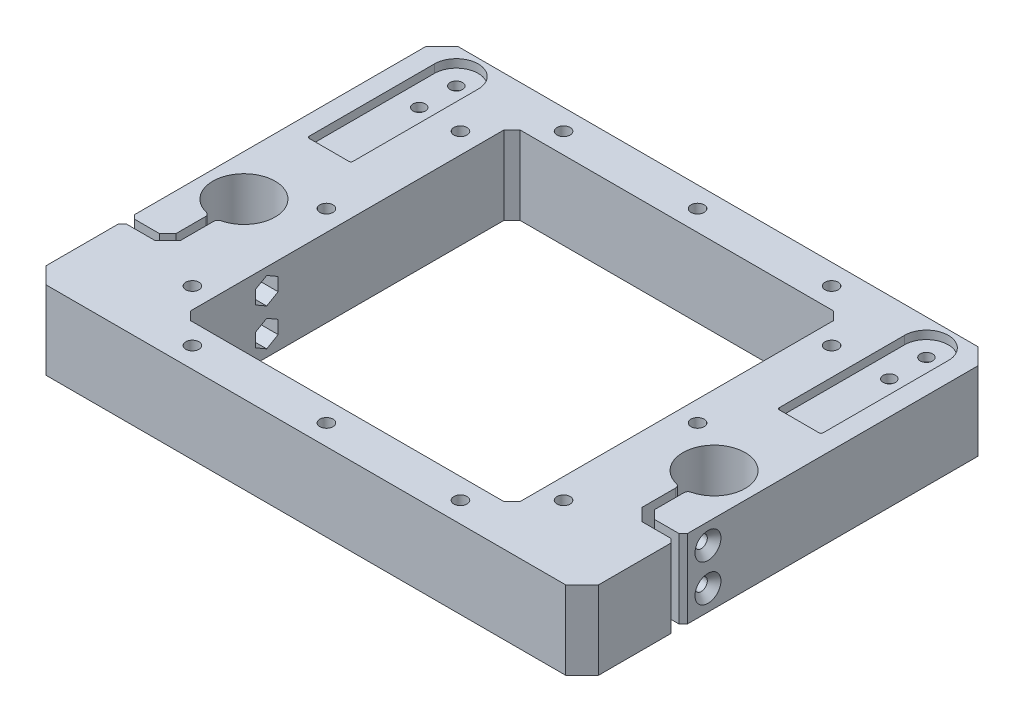
SolidWorks part; units mm, degrees
ref_plane "Front" through (0, 0, 0) normal (0, 0, 1) x (1, 0, 0)
ref_plane "Top" through (0, 0, 0) normal (0, 1, 0) x (1, 0, 0)
ref_plane "Right" through (0, 0, 0) normal (1, 0, 0) x (0, 0, -1)
sketch "Sketch1" plane through (0, 0, 0) normal (0, 1, 0) x (1, 0, 0)
  line L36 (-50, 46) -> (-50, -46)
  line L37 (-46, 50) -> (-50, 46)
  line L38 (46, 50) -> (-46, 50)
  line L39 (50, 46) -> (46, 50)
  line L40 (50, -46) -> (50, 46)
  line L41 (46, -50) -> (50, -46)
  line L42 (-46, -50) -> (46, -50)
  line L43 (-50, -46) -> (-46, -50)
  line L44 (-50, 46) -> (-50, -46)
  line L45 (-46, 50) -> (-50, 46)
  line L46 (46, 50) -> (-46, 50)
  line L47 (50, 46) -> (46, 50)
  line L48 (50, -46) -> (50, 46)
  line L49 (46, -50) -> (50, -46)
  line L50 (-46, -50) -> (46, -50)
  line L51 (-50, -46) -> (-46, -50)
  circle A2 centre (-45, 0) radius 1.6 construction
  circle A5 centre (-45, -32.5) radius 1.6 construction
  circle A6 centre (-32.5, -45) radius 1.6 construction
  circle A7 centre (0, -45) radius 1.6 construction
  circle A8 centre (32.5, -45) radius 1.6 construction
  circle A9 centre (45, -32.5) radius 1.6 construction
  circle A10 centre (45, 0) radius 1.6 construction
  circle A11 centre (45, 32.5) radius 1.6 construction
  circle A12 centre (32.5, 45) radius 1.6 construction
  circle A13 centre (0, 45) radius 1.6 construction
  circle A14 centre (-32.5, 45) radius 1.6 construction
  circle A15 centre (-45, 32.5) radius 1.6 construction
  circle A18 centre (-45, 0) radius 1.6
  circle A21 centre (-45, -32.5) radius 1.6
  circle A22 centre (-32.5, -45) radius 1.6
  circle A23 centre (0, -45) radius 1.6
  circle A24 centre (32.5, -45) radius 1.6
  circle A25 centre (45, -32.5) radius 1.6
  circle A26 centre (45, 0) radius 1.6
  circle A27 centre (45, 32.5) radius 1.6
  circle A28 centre (32.5, 45) radius 1.6
  circle A29 centre (0, 45) radius 1.6
  circle A30 centre (-32.5, 45) radius 1.6
  circle A31 centre (-45, 32.5) radius 1.6
  dimension "D1" = 0
extrude "Boss-Extrude2" add sketch "Sketch1" against normal blind 19
sketch "Sketch3" plane through (0, -19, 0) normal (0, 1, 0) x (1, 0, 0)
  line L1 (-40, -40) -> (40, -40)
  line L2 (-40, -40) -> (-40, 40)
  line L3 (-40, 40) -> (40, 40)
  line L4 (40, -40) -> (40, 40)
  line L5 (-40, -40) -> (40, 40) construction
  line L6 (-40, 40) -> (40, -40) construction
  line L7 (-46, 50) -> (46, 50) construction
  point P0 (0, 0)
  dimension "D1" = 10
extrude "Cut-Extrude2" cut sketch "Sketch3" along normal through all contours L4 L1 L2 L3
chamfer "Chamfer1" distance 2 angle 45 4 edges at (-40, -9.5, 40) (40, -9.5, 40) (40, -9.5, -40) (-40, -9.5, -40)
sketch "Sketch4" plane through (0, 0, 0) normal (0, 1, 0) x (1, 0, 0)
  line L1 (67, 46) -> (67, -46)
  line L3 (50, -46) -> (50, 46)
  line L6 (50, 46) -> (46, 50)
  line L7 (46, 50) -> (63, 50)
  line L8 (63, 50) -> (67, 46)
  line L9 (50, -46) -> (46, -50)
  line L10 (46, -50) -> (63, -50)
  line L11 (63, -50) -> (67, -46)
  dimension "D1" = 17
extrude "Boss-Extrude3" add sketch "Sketch4" against normal up to surface (19 mm away) up to face at (0, -19, 0)
sketch "Sketch5" plane through (0, -19, 0) normal (0, -1, 0) x (1, 0, 0)
  line L0 (67, -46) -> (67, 46) construction
  line L3 (63, -50) -> (-46, -50) construction
  line L4 (50, 46) -> (50, -46) construction
  circle A0 centre (57, -43.5) radius 10 construction
  circle A1 centre (57, -43.5) radius 1.5
  circle A2 centre (57, -34.5) radius 1.5
  circle A3 centre (57, 8) radius 7.55
  dimension "D1" = 3
  dimension "D2" = 9
  dimension "D3" = 15.1
  dimension "D4" = 8
  dimension "D5" = 7
  dimension "D6" = 6.5
extrude "Cut-Extrude3" cut sketch "Sketch5" against normal through all
sketch "Sketch2" plane through (0, -19, 0) normal (0, 1, 0) x (1, 0, 0)
  line L1 (-29.2957, 45) -> (-30.8979, 47.775)
  line L2 (-30.8979, 47.775) -> (-34.1021, 47.775)
  line L3 (-34.1021, 47.775) -> (-35.7043, 45)
  line L4 (-35.7043, 45) -> (-34.1021, 42.225)
  line L5 (-34.1021, 42.225) -> (-30.8979, 42.225)
  line L6 (-30.8979, 42.225) -> (-29.2957, 45)
  line L7 (3.2043, 45) -> (1.6021, 47.775)
  line L8 (1.6021, 47.775) -> (-1.6021, 47.775)
  line L9 (-1.6021, 47.775) -> (-3.2043, 45)
  line L10 (-3.2043, 45) -> (-1.6021, 42.225)
  line L11 (-1.6021, 42.225) -> (1.6021, 42.225)
  line L12 (1.6021, 42.225) -> (3.2043, 45)
  line L13 (35.7043, 45) -> (34.1021, 47.775)
  line L14 (34.1021, 47.775) -> (30.8979, 47.775)
  line L15 (30.8979, 47.775) -> (29.2957, 45)
  line L16 (29.2957, 45) -> (30.8979, 42.225)
  line L17 (30.8979, 42.225) -> (34.1021, 42.225)
  line L18 (34.1021, 42.225) -> (35.7043, 45)
  line L19 (45, 35.7043) -> (42.225, 34.1021)
  line L20 (42.225, 34.1021) -> (42.225, 30.8979)
  line L21 (42.225, 30.8979) -> (45, 29.2957)
  line L22 (45, 29.2957) -> (47.775, 30.8979)
  line L23 (47.775, 30.8979) -> (47.775, 34.1021)
  line L24 (47.775, 34.1021) -> (45, 35.7043)
  line L25 (45, 3.2043) -> (42.225, 1.6021)
  line L26 (42.225, 1.6021) -> (42.225, -1.6021)
  line L27 (42.225, -1.6021) -> (45, -3.2043)
  line L28 (45, -3.2043) -> (47.775, -1.6021)
  line L29 (47.775, -1.6021) -> (47.775, 1.6021)
  line L30 (47.775, 1.6021) -> (45, 3.2043)
  line L31 (45, -29.2957) -> (42.225, -30.8979)
  line L32 (42.225, -30.8979) -> (42.225, -34.1021)
  line L33 (42.225, -34.1021) -> (45, -35.7043)
  line L34 (45, -35.7043) -> (47.775, -34.1021)
  line L35 (47.775, -34.1021) -> (47.775, -30.8979)
  line L36 (47.775, -30.8979) -> (45, -29.2957)
  line L37 (30.8979, -42.225) -> (29.2957, -45)
  line L38 (29.2957, -45) -> (30.8979, -47.775)
  line L39 (30.8979, -47.775) -> (34.1021, -47.775)
  line L40 (34.1021, -47.775) -> (35.7043, -45)
  line L41 (35.7043, -45) -> (34.1021, -42.225)
  line L42 (34.1021, -42.225) -> (30.8979, -42.225)
  line L43 (-1.6021, -42.225) -> (-3.2043, -45)
  line L44 (-3.2043, -45) -> (-1.6021, -47.775)
  line L45 (-1.6021, -47.775) -> (1.6021, -47.775)
  line L46 (1.6021, -47.775) -> (3.2043, -45)
  line L47 (3.2043, -45) -> (1.6021, -42.225)
  line L48 (1.6021, -42.225) -> (-1.6021, -42.225)
  line L49 (-34.1021, -42.225) -> (-35.7043, -45)
  line L50 (-35.7043, -45) -> (-34.1021, -47.775)
  line L51 (-34.1021, -47.775) -> (-30.8979, -47.775)
  line L52 (-30.8979, -47.775) -> (-29.2957, -45)
  line L53 (-29.2957, -45) -> (-30.8979, -42.225)
  line L54 (-30.8979, -42.225) -> (-34.1021, -42.225)
  line L55 (-42.225, -30.8979) -> (-45, -29.2957)
  line L56 (-45, -29.2957) -> (-47.775, -30.8979)
  line L57 (-47.775, -30.8979) -> (-47.775, -34.1021)
  line L58 (-47.775, -34.1021) -> (-45, -35.7043)
  line L59 (-45, -35.7043) -> (-42.225, -34.1021)
  line L60 (-42.225, -34.1021) -> (-42.225, -30.8979)
  line L61 (-45, 3.2043) -> (-47.775, 1.6021)
  line L62 (-47.775, 1.6021) -> (-47.775, -1.6021)
  line L63 (-47.775, -1.6021) -> (-45, -3.2043)
  line L64 (-45, -3.2043) -> (-42.225, -1.6021)
  line L65 (-42.225, -1.6021) -> (-42.225, 1.6021)
  line L66 (-42.225, 1.6021) -> (-45, 3.2043)
  line L67 (-42.225, 34.1021) -> (-45, 35.7043)
  line L68 (-45, 35.7043) -> (-47.775, 34.1021)
  line L69 (-47.775, 34.1021) -> (-47.775, 30.8979)
  line L70 (-47.775, 30.8979) -> (-45, 29.2957)
  line L71 (-45, 29.2957) -> (-42.225, 30.8979)
  line L72 (-42.225, 30.8979) -> (-42.225, 34.1021)
  line L73 (59.775, 45.1021) -> (57, 46.7043)
  line L74 (57, 46.7043) -> (54.225, 45.1021)
  line L75 (54.225, 45.1021) -> (54.225, 41.8979)
  line L76 (54.225, 41.8979) -> (57, 40.2957)
  line L77 (57, 40.2957) -> (59.775, 41.8979)
  line L78 (59.775, 41.8979) -> (59.775, 45.1021)
  line L79 (59.775, 36.1021) -> (57, 37.7043)
  line L80 (57, 37.7043) -> (54.225, 36.1021)
  line L81 (54.225, 36.1021) -> (54.225, 32.8979)
  line L82 (54.225, 32.8979) -> (57, 31.2957)
  line L83 (57, 31.2957) -> (59.775, 32.8979)
  line L84 (59.775, 32.8979) -> (59.775, 36.1021)
  circle A0 centre (-32.5, 45) radius 2.775 construction
  circle A1 centre (0, 45) radius 2.775 construction
  circle A2 centre (32.5, 45) radius 2.775 construction
  circle A3 centre (45, 32.5) radius 2.775 construction
  circle A4 centre (45, 0) radius 2.775 construction
  circle A5 centre (45, -32.5) radius 2.775 construction
  circle A6 centre (32.5, -45) radius 2.775 construction
  circle A7 centre (0, -45) radius 2.775 construction
  circle A8 centre (-32.5, -45) radius 2.775 construction
  circle A9 centre (-45, -32.5) radius 2.775 construction
  circle A10 centre (-45, 0) radius 2.775 construction
  circle A11 centre (-45, 32.5) radius 2.775 construction
  circle A12 centre (57, 43.5) radius 2.775 construction
  circle A13 centre (57, 34.5) radius 2.775 construction
  dimension "D1" = 5.55
extrude "Cut-Extrude1" cut sketch "Sketch2" along normal offset from surface (15 mm away) 4 up to face at (57, 0, -45)
sketch "Sketch6" plane through (0, -19, 0) normal (0, -1, 0) x (1, 0, 0)
  line L1 (67, -46) -> (67, 46) construction
  line L2 (57, 8) -> (57, 18) construction
  line L3 (56, 17.9499) -> (56, 46)
  line L4 (-46, 50) -> (63, 50) construction
  line L5 (56, 46) -> (52, 50)
  line L6 (67, 46) -> (63, 50) construction
  line L7 (52, 50) -> (63, 50)
  line L8 (63, 50) -> (67, 46)
  line L9 (67, 46) -> (67, 8)
  line L10 (56, 17.9499) -> (56, 15.4835)
  line L11 (56, 15.4835) -> (58, 15.4835)
  line L12 (58, 15.4835) -> (58, 17.9499)
  arc A0 (56, 17.9499) -> (67, 8) centre (57, 8) cw construction
  circle A1 centre (57, 8) radius 7.55 construction
  arc A2 (58, 17.9499) -> (67, 8) centre (57, 8) cw
  dimension "D1" = 1
extrude "Cut-Extrude4" cut sketch "Sketch6" against normal through all both and the other way through all
sketch "Sketch7" plane through (0, -19, 0) normal (0, -1, 0) x (1, 0, 0)
  line L0 (67, 25.4835) -> (67, 8)
  line L2 (58, 17.9499) -> (58, 25.4835)
  line L3 (58, 25.4835) -> (67, 25.4835)
  arc A0 (67, 8) -> (58, 17.9499) centre (57, 8) ccw construction
  arc A1 (67, 8) -> (58, 17.9499) centre (57, 8) ccw
  dimension "D1" = 10
extrude "Boss-Extrude4" add sketch "Sketch7" against normal up to surface (19 mm away) up to face at (23.9097, 0, 3.6347)
sketch "Sketch8" plane through (67, 0, 0) normal (1, 0, 0) x (0, 0, -1)
  line L0 (-19.4835, -5) -> (-19.4835, 0) construction
  line L2 (-19.4835, -5) -> (-19.4835, -14) construction
  line L3 (-19.4835, -14) -> (-19.4835, -19) construction
  line L5 (-25.4835, 0) -> (46, 0) construction
  line L6 (46, -19) -> (-25.4835, -19) construction
  circle A0 centre (-19.4835, -5) radius 1.5
  circle A1 centre (-19.4835, -14) radius 1.5
  point P4 (0, 0)
  point P9 (0, 0)
  dimension "D1" = 3
  dimension "D2" = 5
  dimension "D3" = 6
extrude "Cut-Extrude5" cut sketch "Sketch8" against normal through all both and the other way through all
sketch "Sketch9" plane through (40, 0, 0) normal (-1, 0, 0) x (0, 0, 1)
  line L1 (22.2585, -3.3979) -> (19.4835, -1.7957)
  line L2 (19.4835, -1.7957) -> (16.7085, -3.3979)
  line L3 (16.7085, -3.3979) -> (16.7085, -6.6021)
  line L4 (16.7085, -6.6021) -> (19.4835, -8.2043)
  line L5 (19.4835, -8.2043) -> (22.2585, -6.6021)
  line L6 (22.2585, -6.6021) -> (22.2585, -3.3979)
  line L7 (22.2585, -12.3979) -> (19.4835, -10.7957)
  line L8 (19.4835, -10.7957) -> (16.7085, -12.3979)
  line L9 (16.7085, -12.3979) -> (16.7085, -15.6021)
  line L10 (16.7085, -15.6021) -> (19.4835, -17.2043)
  line L11 (19.4835, -17.2043) -> (22.2585, -15.6021)
  line L12 (22.2585, -15.6021) -> (22.2585, -12.3979)
  circle A0 centre (19.4835, -5) radius 2.775 construction
  circle A1 centre (19.4835, -14) radius 2.775 construction
  dimension "D1" = 5.55
extrude "Cut-Extrude6" cut sketch "Sketch9" against normal offset from surface (14 mm away) 2 up to face at (56, -5, 20.9835)
hole_wizard "CSK for M3 Flat Head Machine Screw1" positions "Sketch12" profile "Sketch13" countersink size "M3" standard "ANSI Metric"
sketch "Sketch12" plane through (67, 0, 0) normal (1, 0, 0) x (0, 0, -1)
  point P0 (-19.4835, -5)
  point P3 (-19.4835, -14)
sketch "Sketch13" plane through (67, -5, 19.4835) normal (0, 1, 0) x (0, 0, -1)
  line L0 (0, 0) -> (0, 27.9013)
  line L1 (0, 27.9013) -> (1.5, 27)
  line L2 (1.5, 27) -> (1.5, 1.65)
  line L3 (1.5, 1.65) -> (3.15, 0)
  line L5 (3.15, 0) -> (0, 0)
  line L6 (-1.5, 1.65) -> (-3.15, 0) construction
  line L10 (0, 27.9013) -> (-1.5, 27) construction
  line L11 (0, -6.35) -> (0, 107.95) construction
  dimension "Hole Dia." = 3
  dimension "Hole Depth" = 27
  dimension "Near C'Sink Dia." = 6.3
  dimension "Near C'Sink Angle" = 90
  dimension "Drill Angle" = 118
sketch "Sketch14" plane through (0, -19, 0) normal (0, -1, 0) x (1, 0, 0)
  line L0 (52, 50) -> (56, 46)
  line L1 (56, 46) -> (56, 27.4835)
  line L2 (56, 15.4835) -> (56, 46) construction
  line L3 (56, 27.4835) -> (67, 27.4835)
  line L4 (67, 27.4835) -> (67, 46)
  line L5 (67, 46) -> (63, 50)
  line L6 (63, 50) -> (52, 50)
  line L7 (67, -46) -> (67, 25.4835) construction
  line L8 (67, 25.4835) -> (58, 25.4835) construction
  point P4 (0, 0)
  dimension "D1" = 2
extrude "Boss-Extrude5" add sketch "Sketch14" against normal up to surface (19 mm away) up to face at (23.75, 0, 5.575)
chamfer "Chamfer2" distance 2 angle 45 1 edges at (58, -9.5, 25.4835)
chamfer "Chamfer3" distance 3 angle 45 1 edges at (56, -9.5, 27.4835)
fillet "Fillet3" radius 1 2 edges at (58, -9.5, 15.4835) (56, -9.5, 15.4835)
chamfer "Chamfer4" distance 1 angle 45 2 edges at (67, -9.5, 27.4835) (67, -9.5, 25.4835)
sketch "Sketch10" plane through (0, 0, 0) normal (0, 1, 0) x (1, 0, 0)
  line L0 (62.1, 43.5) -> (62.1, 12.85) construction
  line L1 (62.1, 12.85) -> (51.9, 12.85) construction
  line L2 (51.9, 12.85) -> (51.9, 43.5) construction
  line L3 (51.7, 12.65) -> (51.7, 43.5)
  line L4 (62.3, 43.5) -> (62.3, 12.65)
  line L5 (62.3, 12.65) -> (51.7, 12.65)
  arc A0 (51.9, 43.5) -> (62.1, 43.5) centre (57, 43.5) cw construction
  arc A1 (51.7, 43.5) -> (62.3, 43.5) centre (57, 43.5) cw
  dimension "D1" = 5.1
  dimension "D2" = 30.65
  dimension "D3" = 0.2
extrude "Cut-Extrude7" cut sketch "Sketch10" against normal blind 2
fillet "Fillet2" radius 0.5 2 edges at (62.3, -1, -12.65) (51.7, -1, -12.65)
hole_wizard "CSK for M6 Flat Head Machine Screw1" positions "Sketch15" profile "Sketch16" countersink size "M6" standard "ANSI Metric"
sketch "Sketch15" plane through (0, -19, 0) normal (0, -1, 0) x (-1, 0, 0)
  line L0 (-57, -0.45) -> (-57, 9.55) construction
  arc A0 (-55.2339, -15.3405) -> (-58.7661, -15.3405) centre (-57, -8) ccw construction
  arc A1 (-55.2339, -15.3405) -> (-58.7661, -15.3405) centre (-57, -8) ccw construction
  point P0 (-57, 9.55)
  point P6 (0, 0)
  point P11 (-52.1285, 9.0513)
  point P12 (0, 0)
  dimension "D1" = 10
sketch "Sketch16" plane through (57, -19, -9.55) normal (1, 0, 0) x (0, 0, -1)
  line L0 (0, 0) -> (0, 15.8026)
  line L1 (0, 15.8026) -> (3, 14)
  line L2 (3, 14) -> (3, 3.3)
  line L3 (3, 3.3) -> (6.3, 0)
  line L5 (6.3, 0) -> (0, 0)
  line L6 (-3, 3.3) -> (-6.3, 0) construction
  line L10 (0, 15.8026) -> (-3, 14) construction
  line L11 (0, -6.35) -> (0, 107.95) construction
  dimension "Hole Dia." = 6
  dimension "Hole Depth" = 14
  dimension "Near C'Sink Dia." = 12.6
  dimension "Near C'Sink Angle" = 90
  dimension "Drill Angle" = 118
sketch "Sketch11" plane through (0, 0, -50) normal (0, 0, -1) x (-1, 0, 0)
  line L0 (-63, -19) -> (46, -19) construction
  line L1 (50, 0) -> (0, 0)
  line L2 (50, 0) -> (50, -19)
  line L3 (50, -19) -> (0, -19)
  line L4 (0, 0) -> (0, -19)
extrude "Cut-Extrude8" cut sketch "Sketch11" against normal through all both and the other way through all
mirror "Mirror1" about plane through (0, 0, 50) normal (1, 0, 0) of bodies 122
sketch "Sketch17" plane through (0, -19, 0) normal (0, -1, 0) x (1, 0, 0)
  line L12 (-42.425, 31.0133) -> (-42.425, 33.9867)
  line L13 (-45, 29.5266) -> (-42.425, 31.0133)
  line L14 (-47.575, 31.0133) -> (-45, 29.5266)
  line L15 (-47.575, 33.9867) -> (-47.575, 31.0133)
  line L16 (-45, 35.4734) -> (-47.575, 33.9867)
  line L17 (-42.425, 33.9867) -> (-45, 35.4734)
  line L18 (-42.425, 31.0133) -> (-42.425, 33.9867)
  line L19 (-45, 29.5266) -> (-42.425, 31.0133)
  line L20 (-47.575, 31.0133) -> (-45, 29.5266)
  line L21 (-47.575, 33.9867) -> (-47.575, 31.0133)
  line L22 (-45, 35.4734) -> (-47.575, 33.9867)
  line L23 (-42.425, 33.9867) -> (-45, 35.4734)
  dimension "D1" = 0.2
extrude "Boss-Extrude6" add sketch "Sketch17" against normal blind 5 separate body
